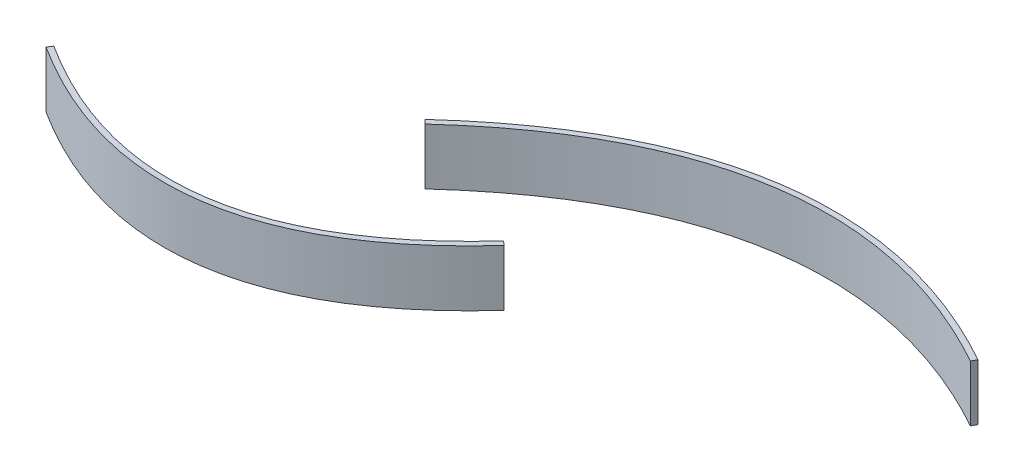
SolidWorks part; units mm, degrees
ref_plane "Front Plane" through (0, 0, 0) normal (0, 0, 1) x (1, 0, 0)
ref_plane "Top Plane" through (0, 0, 0) normal (0, 1, 0) x (1, 0, 0)
ref_plane "Right Plane" through (0, 0, 0) normal (1, 0, 0) x (0, 0, -1)
sketch "Sketch2" plane through (0, 0, 0) normal (0, 1, 0) x (1, 0, 0)
  line L0 (250, 140) -> (650, 140) construction
  line L1 (0, 0) -> (250, 0) construction
  line L2 (0, 0) -> (0, 250) construction
  line L3 (0, 250) -> (250, 250) construction
  line L4 (250, 0) -> (250, 110) construction
  line L5 (650, 140) -> (650, 110)
  line L6 (650, 110) -> (250, 110) construction
  line L7 (250, 140) -> (250, 250) construction
  line L8 (1450, 110) -> (1850, 110) construction
  line L9 (1450, 140) -> (1850, 140) construction
  line L10 (1850, 110) -> (1880, 110) construction
  line L11 (1880, 110) -> (1880, 490) construction
  line L12 (1880, 490) -> (1850, 490)
  line L13 (1850, 490) -> (1850, 140) construction
  line L17 (1680, 690) -> (1630, 690) construction
  line L18 (1680, 660) -> (1630, 660) construction
  line L19 (1630, 660) -> (1630, 690) construction
  line L20 (180, 690) -> (430, 690) construction
  line L21 (430, 690) -> (430, 660) construction
  line L22 (430, 660) -> (180, 660) construction
  line L23 (180, 660) -> (180, 690) construction
  line L24 (374.6283, 501.5653) -> (380, 510)
  line L25 (1087.3976, 603.2713) -> (1080, 610)
  line L26 (830, 720) -> (823.2624, 727.3895)
  line L27 (1680, 840) -> (1684.8645, 848.7371)
  arc A0 (650, 110) -> (859.5238, 185.0495) centre (650, 440) ccw construction
  arc A1 (859.5238, 185.0495) -> (1240.4762, 185.0495) centre (1050, -46.7237) cw construction
  arc A2 (1240.4762, 185.0495) -> (1450, 110) centre (1450, 440) ccw construction
  arc A3 (650, 140) -> (840.4762, 208.2268) centre (650, 440) ccw construction
  arc A4 (840.4762, 208.2268) -> (1259.5238, 208.2268) centre (1050, -46.7237) cw construction
  arc A5 (1259.5238, 208.2268) -> (1450, 140) centre (1450, 440) ccw construction
  arc A8 (1880, 490) -> (1680, 690) centre (1680, 490) ccw construction
  arc A9 (1850, 490) -> (1680, 660) centre (1680, 490) ccw construction
  spline S0 degree 2 poles (380, 510) (765.6485, 264.3979) (1080, 610) knots 0 0 0 1 1 1
  spline S1 degree 1 poles (374.6283, 501.5653) (1087.3976, 603.2713) knots 0 0 1 1 construction
  spline S2 degree 2 poles (830, 720) (1233.9688, 1088.3341) (1680, 840) knots 0 0 0 1 1 1
  spline S3 degree 3 poles (374.6283, 501.5653) (376.6527, 500.276) (380.7208, 497.7077) (388.8241, 492.6818) (398.9423, 486.575) (411.0511, 479.5377) (427.1577, 470.5394) (447.2168, 460.0149) (471.1704, 448.5441) (495.0072, 438.2339) (526.6343, 426.0374) (565.8771, 413.7047) (612.4971, 403.587) (658.6309, 398.1719) (704.2541, 397.4768) (749.3347, 401.5113) (793.8377, 410.2745) (837.7304, 423.7546) (880.9875, 441.9317) (923.5939, 464.7822) (958.5523, 487.6992) (986.192, 508.3477) (1006.7592, 524.9896) (1027.1647, 542.7851) (1044.0355, 558.5747) (1057.4529, 571.7821) (1067.4755, 581.9745) (1075.7971, 590.7103) (1082.4296, 597.8369) (1085.7487, 601.4584) (1087.3976, 603.2713) knots 0 0 0 0 0.007812 0.015625 0.03125 0.046875 0.0625 0.09375 0.125 0.15625 0.1875 0.25 0.3125 0.375 0.4375 0.5 0.5625 0.625 0.6875 0.75 0.8125 0.84375 0.875 0.90625 0.9375 0.953125 0.96875 0.984375 0.992188 1 1 1 1
  spline S4 degree 1 poles (823.2624, 727.3895) (1684.8645, 848.7371) knots 0 0 1 1 construction
  spline S5 degree 3 poles (823.2624, 727.3895) (825.3777, 729.3182) (829.6301, 733.1686) (838.1222, 740.7504) (848.7596, 750.0463) (861.5457, 760.8979) (878.6274, 774.9667) (900.0403, 791.8003) (925.8344, 810.7963) (951.7277, 828.5867) (986.3848, 850.6982) (1029.9562, 875.3171) (1082.6417, 900.0138) (1135.7228, 919.85) (1189.1898, 934.8113) (1243.0279, 944.8849) (1297.2176, 950.0622) (1351.737, 950.3399) (1406.5645, 945.7206) (1461.6809, 936.2123) (1507.8399, 924.2244) (1544.8996, 912.2022) (1572.7601, 901.9714) (1600.6857, 890.528) (1624.0112, 879.9828) (1642.7045, 870.9418) (1656.7399, 863.8593) (1668.4523, 857.7041) (1677.8247, 852.6322) (1682.5242, 850.0401) (1684.8645, 848.7371) knots 0 0 0 0 0.007812 0.015625 0.03125 0.046875 0.0625 0.09375 0.125 0.15625 0.1875 0.25 0.3125 0.375 0.4375 0.5 0.5625 0.625 0.6875 0.75 0.8125 0.84375 0.875 0.90625 0.9375 0.953125 0.96875 0.984375 0.992188 1 1 1 1
  point P36 (430, 675)
  dimension "D8" = 300
  dimension "D9" = 300
  dimension "D12" = 50
  dimension "D4" = 200
  dimension "D19" = 400
  dimension "D1" = 250
  dimension "D2" = 250
  dimension "D3" = 30
  dimension "D5" = 400
  dimension "D6" = 800
  dimension "D7" = 400
  dimension "D10" = 30
  dimension "D11" = 350
  dimension "D13" = 1200
  dimension "D14" = 250
  dimension "D15" = 150
  dimension "D16" = 150
  dimension "D17" = 50
  dimension "D18" = 50
  dimension "D20" = 250
  dimension "D21" = 299.5902
  dimension "D22" = 300
  dimension "D23" = 250
  dimension "D24" = 30
  dimension "D25" = 550
  dimension "D26" = 50
  dimension "D27" = 10
  dimension "D28" = 10
extrude "Boss-Extrude1" add sketch "Sketch2" along normal blind 100 contours L23 L22 L21 L20 | S2 L27 S5 L26 | S0 L25 S3 L24
